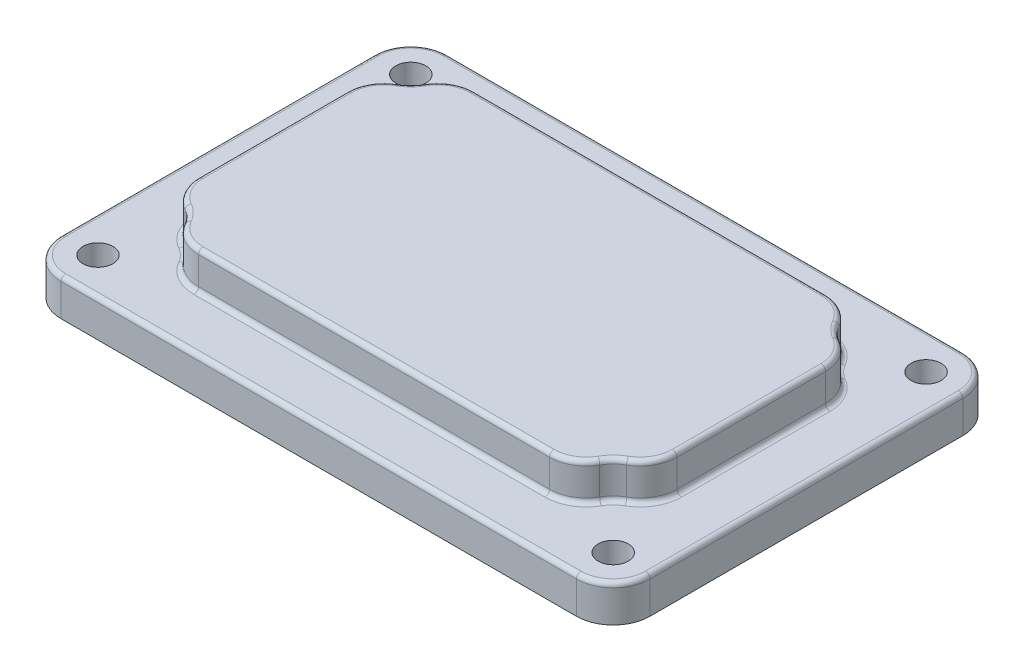
SolidWorks part; units mm, degrees
material "Cast Alloy Steel"
ref_plane "Front Plane" through (0, 0, 0) normal (0, 0, 1) x (1, 0, 0)
ref_plane "Top Plane" through (0, 0, 0) normal (0, 1, 0) x (1, 0, 0)
ref_plane "Right Plane" through (0, 0, 0) normal (1, 0, 0) x (0, 0, -1)
sketch "Extrude Sketch" plane through (0, 0, 0) normal (0, 1, 0) x (1, 0, 0)
  line L1 (44.45, -33.3375) -> (-44.45, -33.3375)
  line L2 (50.8, -26.9875) -> (50.8, 26.9875)
  line L3 (44.45, 33.3375) -> (-44.45, 33.3375)
  line L4 (-50.8, -26.9875) -> (-50.8, 26.9875)
  line L5 (50.8, -33.3375) -> (-50.8, 33.3375) construction
  line L6 (50.8, 33.3375) -> (-50.8, -33.3375) construction
  arc A0 (50.8, 26.9875) -> (44.45, 33.3375) centre (44.45, 26.9875) ccw
  arc A1 (44.45, -33.3375) -> (50.8, -26.9875) centre (44.45, -26.9875) ccw
  arc A2 (-44.45, -33.3375) -> (-50.8, -26.9875) centre (-44.45, -26.9875) cw
  arc A3 (-44.45, 33.3375) -> (-50.8, 26.9875) centre (-44.45, 26.9875) ccw
  point P0 (0, 0)
  dimension "D3" = 6.35
  dimension "D1" = 101.6
  dimension "D2" = 66.675
extrude "Base Extrude" add sketch "Extrude Sketch" along normal blind 6.35
sketch "Boss Sketch" plane through (0, 6.35, 0) normal (0, 1, 0) x (1, 0, 0)
  line L12 (41.275, 23.8125) -> (-41.275, 23.8125)
  line L13 (-41.275, 23.8125) -> (-41.275, -23.8125)
  line L14 (-41.275, -23.8125) -> (41.275, -23.8125)
  line L15 (41.275, -23.8125) -> (41.275, 23.8125)
  line L16 (41.275, 23.8125) -> (-41.275, 23.8125)
  line L17 (-41.275, 23.8125) -> (-41.275, -23.8125)
  line L18 (-41.275, -23.8125) -> (41.275, -23.8125)
  line L19 (41.275, -23.8125) -> (41.275, 23.8125)
  dimension "D1" = 9.525
extrude "Top Boss" add sketch "Boss Sketch" along normal blind 6.35 contours L16 L17 L18 L19
sketch "Base Sketch" plane through (0, 12.7, 0) normal (0, 1, 0) x (1, 0, 0)
  line L0 (0, 0) -> (50.8, 0) construction
  line L1 (50.8, -26.9875) -> (50.8, 26.9875) construction
  line L2 (0, 0) -> (0, 33.3375) construction
  line L3 (44.45, 33.3375) -> (-44.45, 33.3375) construction
  circle A0 centre (41.275, 23.8125) radius 6.35
  circle A1 centre (-41.275, 23.8125) radius 6.35
  circle A2 centre (41.275, -23.8125) radius 6.35
  circle A3 centre (-41.275, -23.8125) radius 6.35
  dimension "D1" = 12.7
extrude "Base Cut" cut sketch "Base Sketch" against normal up to surface (6.35 mm away) up to face at (0, 6.35, 0)
fillet "Fillet" radius 6.35 8 edges at (-41.275, 9.525, -17.4625) (-34.925, 9.525, -23.8125) (41.275, 9.525, -17.4625) (34.925, 9.525, -23.8125) (41.275, 9.525, 17.4625) (34.925, 9.525, 23.8125) (-34.925, 9.525, 23.8125) (-41.275, 9.525, 17.4625)
shell "Shell" thickness 3.175
sketch "Corner Sketch" plane through (0, 3.175, 0) normal (0, -1, 0) x (-1, 0, 0)
  line L0 (48.9401, -31.4776) -> (44.45, -26.9875)
  circle A4 centre (44.45, -26.9875) radius 6.35
  circle A5 centre (-44.45, -26.9875) radius 6.35
  circle A6 centre (-44.45, 26.9875) radius 6.35
  circle A7 centre (44.45, 26.9875) radius 6.35
  arc A8 (44.45, -33.3375) -> (50.8, -26.9875) centre (44.45, -26.9875) ccw construction
  point P5 (48.9401, -31.4776)
  dimension "D1" = 12.7
extrude "Corner Extrude" add sketch "Corner Sketch" along normal up to surface (3.175 mm away) contours A5 | A4 | A7 | A6 up to face at (0, 0, 0)
fillet "Shell Fillet" radius 0.7874 56 edges at (-39.9599, 0, 22.4974) (-39.9599, 3.175, 22.4974) (39.9599, 3.175, 22.4974) (39.9599, 0, 22.4974) (-39.9599, 0, -22.4974) (-39.9599, 3.175, -22.4974) (39.9599, 0, -22.4974) (39.9599, 3.175, -22.4974) (38.1, 3.175, 0) (0, 3.175, -20.6375) (-38.1, 3.175, 0) (0, 3.175, 20.6375) (-38.1, 9.525, 0) (0, 9.525, 20.6375) (38.1, 9.525, 0) (0, 9.525, -20.6375) (34.5398, 3.175, -17.0773) (34.5398, 9.525, -17.0773) (-34.5398, 9.525, 17.0773) (-34.5398, 3.175, 17.0773) (34.5398, 9.525, 17.0773) (34.5398, 3.175, 17.0773) (-34.5398, 9.525, -17.0773) (-34.5398, 3.175, -17.0773) (-37.6746, 3.175, -14.4015) (-37.6746, 9.525, -14.4015) (-31.864, 9.525, -20.2121) (-31.864, 3.175, -20.2121) (37.6746, 9.525, -14.4015) (37.6746, 3.175, -14.4015) (31.864, 3.175, -20.2121) (31.864, 9.525, -20.2121) (37.6746, 3.175, 14.4015) (37.6746, 9.525, 14.4015) (31.864, 9.525, 20.2121) (31.864, 3.175, 20.2121) (-31.864, 3.175, 20.2121) (-31.864, 9.525, 20.2121) (-37.6746, 9.525, 14.4015) (-37.6746, 3.175, 14.4015) (38.9507, 1.5875, 30.1625) (0, 3.175, 30.1625) (-38.9507, 1.5875, 30.1625) (0, 0, 30.1625) (-47.625, 1.5875, 21.4882) (-47.625, 3.175, 0) (-47.625, 1.5875, -21.4882) (-47.625, 0, 0) (47.625, 1.5875, 21.4882) (47.625, 0, 0) (47.625, 1.5875, -21.4882) (47.625, 3.175, 0) (-38.9507, 1.5875, -30.1625) (0, 3.175, -30.1625) (38.9507, 1.5875, -30.1625) (0, 0, -30.1625)
hole_wizard "Diameter Hole" positions "Hole Width" profile "Hole Depth" hole size "#6" standard "ANSI Inch" end condition through all
sketch "Hole Width" plane through (0, 6.35, 0) normal (0, 1, 0) x (1, 0, 0)
  point P0 (-44.45, 26.9875)
  point P3 (44.45, 26.9875)
  point P6 (44.45, -26.9875)
  point P9 (-44.45, -26.9875)
sketch "Hole Depth" plane through (-44.45, 6.35, -26.9875) normal (1, 0, 0) x (0, 0, 1)
  line L0 (0, 0) -> (0, 6.35)
  line L1 (0, 6.35) -> (2.5908, 6.35)
  line L2 (2.5908, 6.35) -> (2.5908, 0)
  line L5 (2.5908, 0) -> (0, 0)
  line L11 (0, -6.35) -> (0, 107.95) construction
  dimension "Thru Hole Dia." = 5.1816
  dimension "Thru Hole Depth" = 6.35
fillet "Edge Fillet" radius 0.7874 16 edges at (-33.4515, 12.7, -22.9618) (0, 12.7, -23.8125) (33.4515, 12.7, -22.9618) (36.7849, 12.7, -19.3224) (40.4243, 12.7, -15.989) (41.275, 12.7, 0) (40.4243, 12.7, 15.989) (36.7849, 12.7, 19.3224) (33.4515, 12.7, 22.9618) (0, 12.7, 23.8125) (-33.4515, 12.7, 22.9618) (-36.7849, 12.7, 19.3224) (-40.4243, 12.7, 15.989) (-41.275, 12.7, 0) (-40.4243, 12.7, -15.989) (-36.7849, 12.7, -19.3224)
fillet "Inner Fillet" radius 0.7874 8 edges at (-48.9401, 6.35, 31.4776) (-50.8, 6.35, 0) (-48.9401, 6.35, -31.4776) (0, 6.35, -33.3375) (48.9401, 6.35, -31.4776) (48.9401, 6.35, 31.4776) (50.8, 6.35, 0) (0, 6.35, 33.3375)
fillet "Outer Fillet" radius 0.7874 16 edges at (33.4515, 6.35, 22.9618) (36.7849, 6.35, 19.3224) (40.4243, 6.35, 15.989) (0, 6.35, 23.8125) (41.275, 6.35, 0) (40.4243, 6.35, -15.989) (36.7849, 6.35, -19.3224) (33.4515, 6.35, -22.9618) (-33.4515, 6.35, -22.9618) (0, 6.35, -23.8125) (-36.7849, 6.35, -19.3224) (-40.4243, 6.35, -15.989) (-41.275, 6.35, 0) (-40.4243, 6.35, 15.989) (-36.7849, 6.35, 19.3224) (-33.4515, 6.35, 22.9618)
